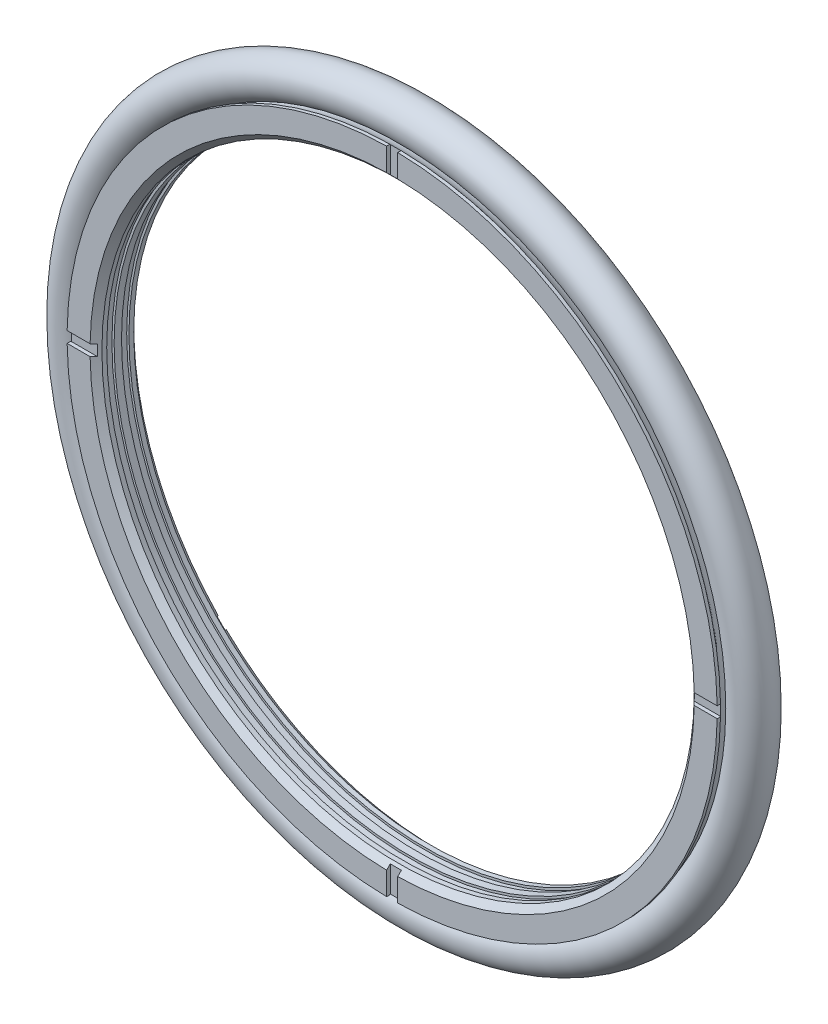
SolidWorks part; units mm, degrees
material "PTFE+NBR"
ref_plane "Front Plane" through (0, 0, 0) normal (0, 0, 1) x (1, 0, 0)
ref_plane "Top Plane" through (0, 0, 0) normal (0, 1, 0) x (1, 0, 0)
ref_plane "Right Plane" through (0, 0, 0) normal (1, 0, 0) x (0, 0, -1)
sketch "Sketch1" plane through (0, 0, 0) normal (1, 0, 0) x (0, 0, -1)
  line L0 (0, 0) -> (70.1333, 0) construction
  line L1 (0, 0) -> (0, 74.4081) construction
  line L2 (-2.15, 40) -> (-1.5, 40)
  line L3 (2.95, 40.8) -> (2.95, 43.9)
  line L4 (2.95, 43.9) -> (2.5, 43.9)
  line L5 (-2.95, 43.9) -> (-2.5, 43.9)
  line L6 (-2.95, 40.8) -> (-2.95, 43.9)
  line L7 (-1.5, 40) -> (-1.5, 40.3)
  line L8 (-1.5, 40.3) -> (-0.5, 40.3)
  line L9 (-0.5, 40.3) -> (-0.5, 40)
  line L10 (1.5, 40) -> (2.15, 40)
  line L11 (-2.15, 40) -> (-2.95, 40.8)
  line L12 (2.15, 40) -> (2.95, 40.8)
  line L13 (-0.5, 40) -> (0.5, 40)
  line L14 (0.5, 40.3) -> (0.5, 40)
  line L15 (1.5, 40.3) -> (0.5, 40.3)
  line L16 (1.5, 40) -> (1.5, 40.3)
  arc A0 (-2.5, 43.9) -> (2.5, 43.9) centre (0, 45.6626) ccw
  point P5 (2.95, 40)
  point P10 (-2.95, 40)
  point P11 (0, 60)
  point P25 (0, 40)
  dimension "D6" = 3.0589
  dimension "D5" = 1
  dimension "D1" = 5.9
  dimension "D3" = 80
  dimension "D4" = 87.8
  dimension "D7" = 1
  dimension "D8" = 0.8
  dimension "D9" = 45
  dimension "D10" = 0.8
  dimension "D11" = 45
  dimension "D12" = 0.3
  dimension "D13" = 5
revolve "Revolve1" add sketch "Sketch1" angle 360 about L0
sketch "Sketch4" plane through (0, 0, 2.95) normal (0, 0, 1) x (1, 0, 0)
  line L0 (0, 0) -> (0, 54.67) construction
  line L1 (-0.75, 50.4268) -> (0.75, 50.4268)
  line L2 (-0.75, 50.4268) -> (-0.75, 33.977)
  line L3 (-0.75, 33.977) -> (0.75, 33.977)
  line L4 (0.75, 50.4268) -> (0.75, 33.977)
  dimension "D1" = 1.5
  dimension "D2" = 33.977
  dimension "D3" = 16.4498
extrude "Cut-Extrude1" cut sketch "Sketch4" against normal blind 0.5
sketch "Sketch5" plane through (0, 0, -2.95) normal (0, 0, -1) x (-1, 0, 0)
  line L0 (0, 0) -> (40.9381, 40.9381) construction
  line L1 (0, 0) -> (61.4907, 0) construction
  line L2 (33.604, 32.5433) -> (32.5433, 33.604)
  line L3 (32.5433, 33.604) -> (24.9255, 25.9862)
  line L4 (24.9255, 25.9862) -> (25.9862, 24.9255)
  line L5 (33.604, 32.5433) -> (25.9862, 24.9255)
  point P9 (25.4558, 25.4558)
  point P10 (33.0737, 33.0737)
  dimension "D1" = 45
  dimension "D2" = 1.5
  dimension "D3" = 10.7732
  dimension "D4" = 36
extrude "Cut-Extrude2" cut sketch "Sketch5" against normal blind 0.5
pattern_circular "CirPattern1" count 4 over 360 about axis through (0, 0, 0) along (0, 0, 1) of "Cut-Extrude1", "Cut-Extrude2"
sketch "Sketch2" plane through (0, 0, 0) normal (1, 0, 0) x (0, 0, -1)
  line L0 (0, 0) -> (29.2798, 0) construction
  circle A0 centre (0, 45.85) radius 2.65
  dimension "D1" = 97
  dimension "D2" = 5.3
revolve "Revolve2" add sketch "Sketch2" angle 360 about L0
